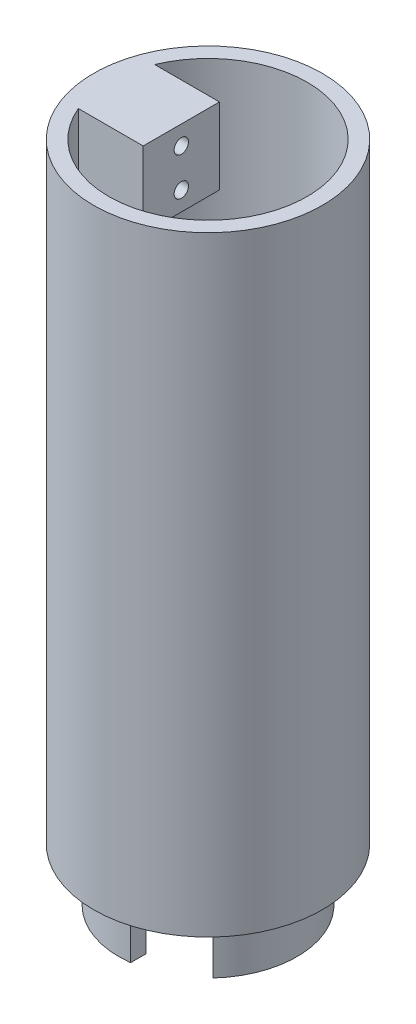
SolidWorks part; units mm, degrees
ref_plane "Front Plane" through (0, 0, 0) normal (0, 0, 1) x (1, 0, 0)
ref_plane "Top Plane" through (0, 0, 0) normal (0, 1, 0) x (1, 0, 0)
ref_plane "Right Plane" through (0, 0, 0) normal (1, 0, 0) x (0, 0, -1)
sketch "Sketch1" plane through (0, 0, 0) normal (0, 1, 0) x (1, 0, 0)
  circle A0 centre (0, 0) radius 19.05
  dimension "D1" = 38.1
extrude "Boss-Extrude1" add sketch "Sketch1" along normal mid plane 101.6
sketch "Sketch2" plane through (0, -50.8, 0) normal (0, -1, 0) x (1, 0, 0)
  circle A0 centre (0, 0) radius 15.0813 construction
  circle A1 centre (0, 0) radius 15.0813 construction
  circle A2 centre (0, 0) radius 14.8273
  dimension "D1" = 0.254
extrude "Boss-Extrude2" add sketch "Sketch2" along normal blind 8.89
sketch "Sketch4" plane through (0, 50.8, 0) normal (0, 1, 0) x (1, 0, 0)
  circle A0 centre (0, 0) radius 16.51
  circle A1 centre (0, 0) radius 19.05 construction
  dimension "D1" = 2.54
extrude "Cut-Extrude2" cut sketch "Sketch4" against normal offset from surface 6.35 and the other way through all up to face at (0, -50.8, -14.8273)
sketch "Sketch5" plane through (0, -59.69, 0) normal (0, -1, 0) x (1, 0, 0)
  circle A0 centre (0, 0) radius 12.2873
  circle A1 centre (0, 0) radius 14.8273 construction
  dimension "D1" = 2.54
extrude "Cut-Extrude3" cut sketch "Sketch5" against normal up to next
sketch "Sketch8" plane through (0, 0, 0) normal (1, 0, 0) x (0, 0, -1)
  line L0 (19.05, 50.8) -> (-19.05, 50.8) construction
  line L1 (-6.35, 38.1) -> (6.35, 38.1)
  line L2 (-6.35, 38.1) -> (-6.35, 50.8)
  line L3 (-6.35, 50.8) -> (6.35, 50.8)
  line L4 (6.35, 38.1) -> (6.35, 50.8)
  line L5 (-6.35, 38.1) -> (6.35, 50.8) construction
  line L6 (-6.35, 50.8) -> (6.35, 38.1) construction
  point P0 (0, 44.45)
  point P7 (0, 0)
  dimension "D1" = 12.7
  dimension "D2" = 12.7
extrude "Boss-Extrude3" add sketch "Sketch8" against normal up to surface (10.795 mm away) from surface
sketch "Sketch9" plane through (0, 0, 0) normal (0, 0, 1) x (1, 0, 0)
  line L0 (-19.05, -50.8) -> (19.05, -50.8) construction
  line L1 (1.827, -59.69) -> (10.873, -59.69)
  line L2 (1.827, -59.69) -> (1.827, -52.07)
  line L3 (1.827, -52.07) -> (10.873, -52.07)
  line L4 (10.873, -59.69) -> (10.873, -52.07)
  line L5 (1.827, -59.69) -> (10.873, -52.07) construction
  line L6 (1.827, -52.07) -> (10.873, -59.69) construction
  line L7 (-14.8273, -59.69) -> (14.8273, -59.69) construction
  circle A0 centre (6.35, -55.88) radius 3.175 construction
  circle A1 centre (6.35, -55.88) radius 3.175 construction
  point P0 (6.35, -55.88)
  point P7 (0, 0)
  point P13 (0, 0)
  point P14 (0, 0)
  point P15 (10.873, -59.69)
  dimension "D2" = 1.27
extrude "Cut-Extrude5" cut sketch "Sketch9" against normal through all both and the other way through all
sketch "Sketch10" plane through (0, -59.69, 0) normal (0, -1, 0) x (1, 0, 0)
  line L1 (2.0044, -1.905) -> (14.7044, -1.905)
  line L2 (2.0044, -1.905) -> (2.0044, 1.905)
  line L3 (2.0044, 1.905) -> (14.7044, 1.905)
  line L4 (14.7044, -1.905) -> (14.7044, 1.905)
  line L5 (2.0044, -1.905) -> (14.7044, 1.905) construction
  line L6 (2.0044, 1.905) -> (14.7044, -1.905) construction
  arc A0 (10.873, -10.0809) -> (10.873, 10.0809) centre (0, 0) ccw construction
  point P0 (8.3544, 0)
  point P5 (0, 0)
  point P7 (0, 0)
  point P11 (0, 0)
  dimension "D1" = 12.7
  dimension "D2" = 3.81
extrude "Boss-Extrude4" add sketch "Sketch10" against normal up to surface (7.62 mm away) up to face at (6.6441, -52.07, 11.1369)
sketch "Sketch11" plane through (0, 0, 1.905) normal (0, 0, 1) x (1, 0, 0)
  circle A0 centre (6.35, -55.88) radius 2.4 construction
  circle A1 centre (6.35, -55.88) radius 2.4
extrude "Cut-Extrude6" cut sketch "Sketch11" against normal through all both and the other way through all
sketch "Sketch12" plane through (-4.445, 0, 0) normal (1, 0, 0) x (0, 0, -1)
  circle A0 centre (0, 41.275) radius 1.2 construction
  circle A1 centre (0, 47.625) radius 1.2 construction
  circle A2 centre (0, 41.275) radius 1.2
  circle A3 centre (0, 47.625) radius 1.2
extrude "Cut-Extrude7" cut sketch "Sketch12" against normal through all
ref_plane "Plane1" through (-25.4, 0, 0) normal (-1, 0, 0) x (0, 0, 1)
sketch "Sketch14" plane through (-25.4, 0, 0) normal (-1, 0, 0) x (0, 0, 1)
  line L0 (0, 41.275) -> (0, 47.625) construction
  line L1 (-2.921, 41.275) -> (-2.921, 47.625)
  line L2 (2.921, 41.275) -> (2.921, 47.625)
  arc A0 (-2.921, 41.275) -> (2.921, 41.275) centre (0, 41.275) ccw
  arc A1 (2.921, 47.625) -> (-2.921, 47.625) centre (0, 47.625) ccw
  point P4 (0, 44.45)
  dimension "D1" = 5.842
extrude "Cut-Extrude8" cut sketch "Sketch14" against normal offset from surface (15.845 mm away) 14
